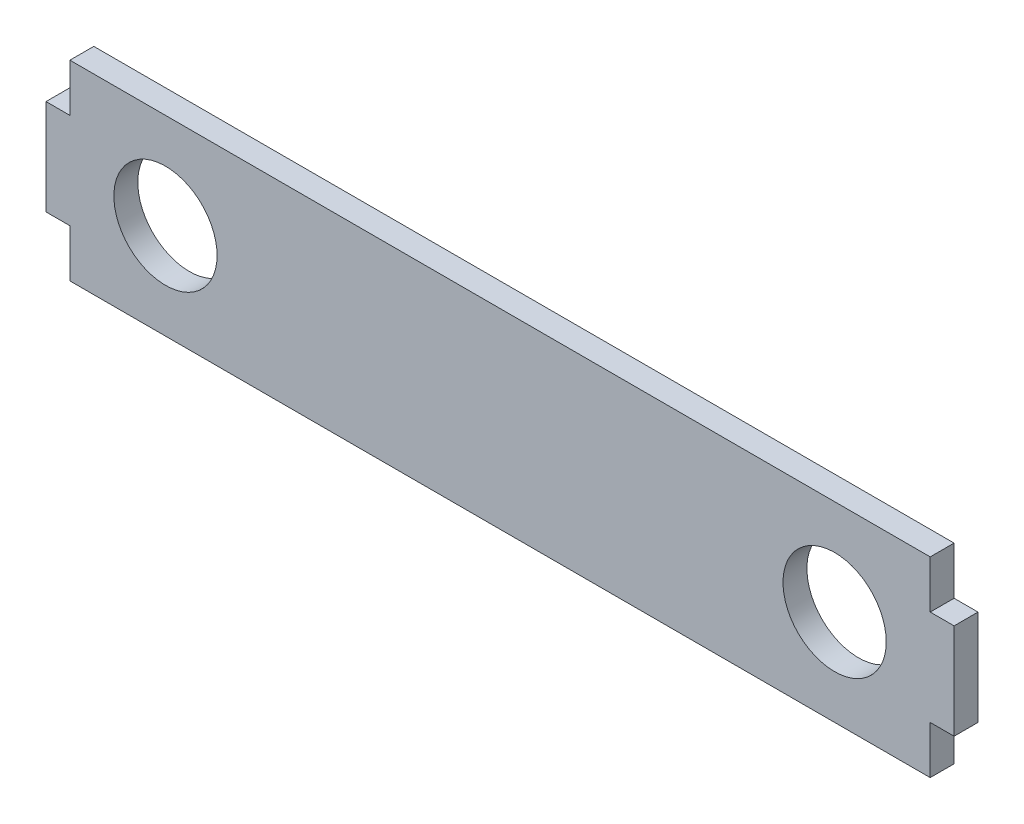
SolidWorks part; units mm, degrees
material "AISI 4130 Steel, annealed at 865C"
ref_plane "X-Y Datum" through (0, 0, 0) normal (0, 0, 1) x (1, 0, 0)
ref_plane "X-Z Datum" through (0, 0, 0) normal (0, 1, 0) x (1, 0, 0)
ref_plane "Y-Z Datum" through (0, 0, 0) normal (1, 0, 0) x (0, 0, -1)
sketch "Sketch1" plane through (0, 0, 0) normal (0, 0, 1) x (1, 0, 0)
  line L0 (30.1625, 0) -> (0, 0) construction
  line L1 (0, 0) -> (0, 6.35) construction
  line L2 (30.1625, -3.175) -> (28.575, -3.175)
  line L3 (28.575, -3.175) -> (28.575, -6.35)
  line L5 (30.1625, 6.35) -> (-30.1625, 6.35)
  line L6 (-30.1625, -6.35) -> (30.1625, -6.35)
  line L16 (30.1625, -6.35) -> (30.1625, 6.35)
  line L17 (-30.1625, 6.35) -> (-30.1625, -6.35)
  line L18 (28.575, 3.175) -> (30.1625, 3.175)
  line L19 (-30.1625, -3.175) -> (-28.575, -3.175)
  line L20 (-28.575, -3.175) -> (-28.575, -6.35)
  line L21 (-28.575, 3.175) -> (-30.1625, 3.175)
  line L22 (28.575, 3.175) -> (28.575, 6.35)
  line L23 (-28.575, 3.175) -> (-28.575, 6.35)
  circle A4 centre (22.225, 0) radius 3.429 construction
  circle A5 centre (22.225, 0) radius 3.429
  circle A6 centre (-22.225, 0) radius 3.429 construction
  circle A7 centre (-22.225, 0) radius 3.429
  dimension "D1" = 12.7
  dimension "D2" = 1.5875
  dimension "D3" = 60.325
  dimension "D4" = 6.35
extrude "Boss-Extrude1" add sketch "Sketch1" against normal blind 1.5875
